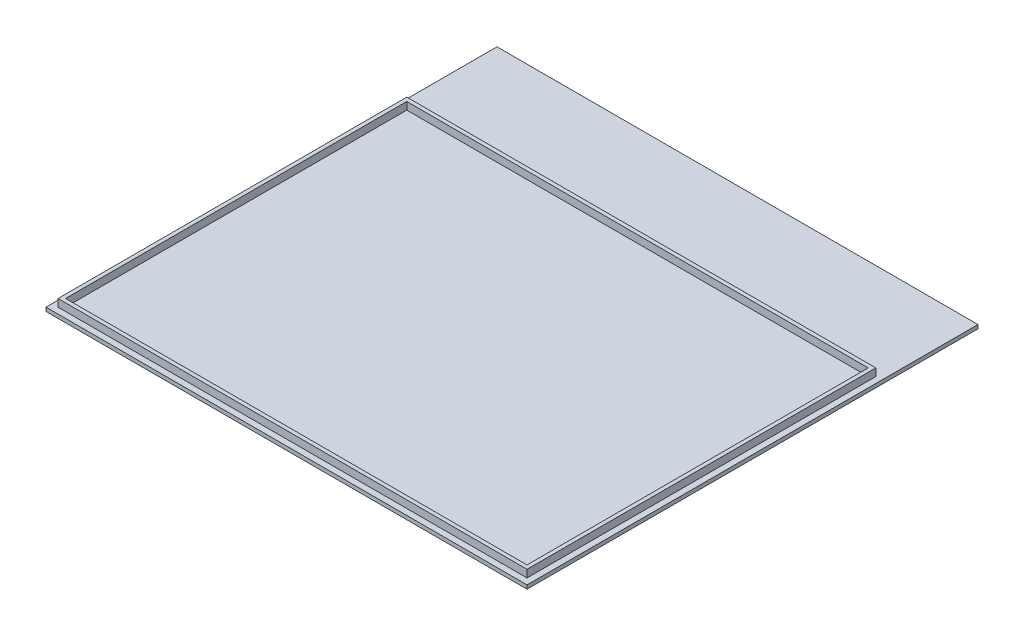
SolidWorks part; units mm, degrees
ref_plane "Front Plane" through (0, 0, 0) normal (0, 0, 1) x (1, 0, 0)
ref_plane "Top Plane" through (0, 0, 0) normal (0, 1, 0) x (1, 0, 0)
ref_plane "Right Plane" through (0, 0, 0) normal (1, 0, 0) x (0, 0, -1)
sketch "Sketch1" plane through (0, 0, 0) normal (0, 1, 0) x (1, 0, 0)
  line L1 (-101.6, -76.2) -> (101.6, -76.2)
  line L2 (-101.6, -76.2) -> (-101.6, 76.2)
  line L3 (-101.6, 76.2) -> (101.6, 76.2)
  line L4 (101.6, -76.2) -> (101.6, 76.2)
  line L5 (-101.6, -76.2) -> (101.6, 76.2) construction
  line L6 (-101.6, 76.2) -> (101.6, -76.2) construction
  point P0 (0, 0)
  dimension "D1" = 203.2
  dimension "D2" = 152.4
extrude "Boss-Extrude1" add sketch "Sketch1" along normal blind 1.5875
sketch "Sketch2" plane through (0, 1.5875, 0) normal (0, 1, 0) x (1, 0, 0)
  line L0 (-101.6, 76.2) -> (-101.6, -76.2) construction
  line L1 (-99.06, 73.66) -> (99.06, 73.66)
  line L2 (-99.06, 73.66) -> (-99.06, -73.66)
  line L3 (-99.06, -73.66) -> (99.06, -73.66)
  line L4 (99.06, 73.66) -> (99.06, -73.66)
  line L5 (101.6, 76.2) -> (-101.6, 76.2) construction
  line L6 (101.6, -76.2) -> (101.6, 76.2) construction
  line L7 (-101.6, -76.2) -> (101.6, -76.2) construction
  dimension "D1" = 2.54
  dimension "D2" = 2.54
  dimension "D3" = 2.54
  dimension "D4" = 2.54
extrude "Boss-Extrude2" add sketch "Sketch2" along normal blind 3.175
sketch "Sketch3" plane through (0, 4.7625, 0) normal (0, 1, 0) x (1, 0, 0)
  line L0 (-99.06, 73.66) -> (-99.06, -73.66) construction
  line L1 (-97.4725, 72.0725) -> (97.4725, 72.0725)
  line L2 (-97.4725, 72.0725) -> (-97.4725, -72.0725)
  line L3 (-97.4725, -72.0725) -> (97.4725, -72.0725)
  line L4 (97.4725, 72.0725) -> (97.4725, -72.0725)
  line L5 (99.06, 73.66) -> (-99.06, 73.66) construction
  line L6 (99.06, -73.66) -> (99.06, 73.66) construction
  line L7 (-99.06, -73.66) -> (99.06, -73.66) construction
  dimension "D1" = 1.5875
  dimension "D2" = 1.5875
  dimension "D3" = 1.5875
  dimension "D4" = 1.5875
extrude "Cut-Extrude1" cut sketch "Sketch3" against normal blind 3.175
sketch "Sketch4" plane through (0, 0, 0) normal (0, -1, 0) x (1, 0, 0)
  line L0 (90.8128, 63.5) -> (44.365, 63.5) construction
  line L1 (-101.6, 76.2) -> (101.6, 76.2) construction
  line L2 (101.6, 76.2) -> (101.6, -76.2) construction
  text T0 "<b>AHCS</b>" font "Dubai" height in points 28
  point P5 (0, 0)
  dimension "D1" = 12.7
  dimension "D2" = 10.7872
extrude "Cut-Extrude2" cut sketch "Sketch4" against normal blind 1
sketch "Sketch5" plane through (0, 0, -76.2) normal (0, 0, -1) x (-1, 0, 0)
  line L1 (-101.6, 1.5875) -> (101.6, 1.5875)
  line L2 (-101.6, 1.5875) -> (-101.6, 0)
  line L3 (-101.6, 0) -> (101.6, 0)
  line L4 (101.6, 1.5875) -> (101.6, 0)
extrude "Boss-Extrude3" add sketch "Sketch5" along normal blind 38.1
